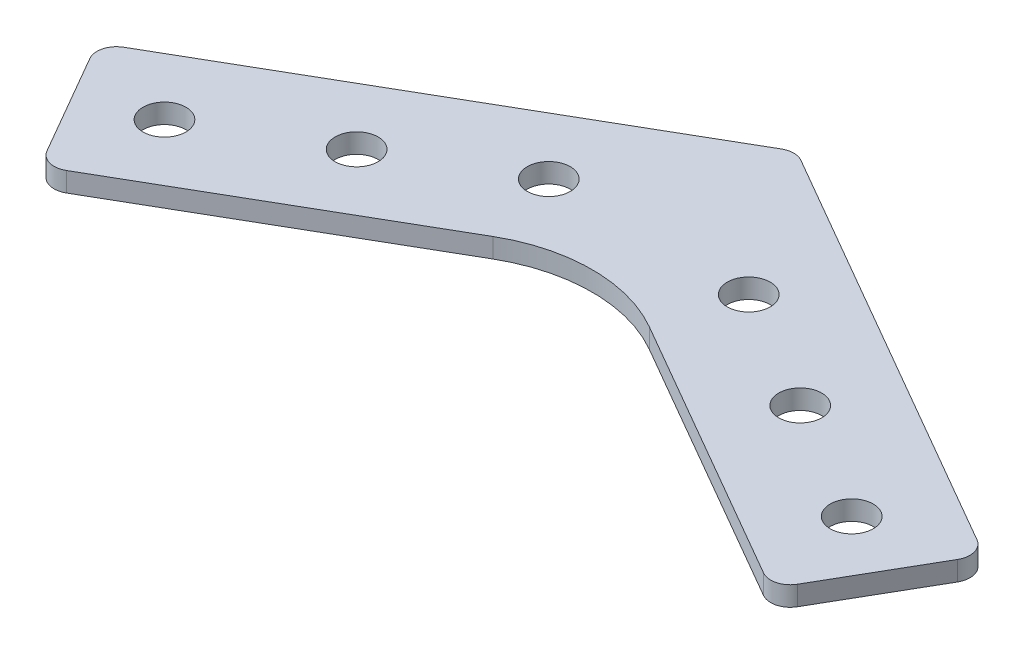
SolidWorks part; units mm, degrees
material "5052-H32"
ref_plane "Front Plane" through (0, 0, 0) normal (0, 0, 1) x (1, 0, 0)
ref_plane "Top Plane" through (0, 0, 0) normal (0, 1, 0) x (1, 0, 0)
ref_plane "Right Plane" through (0, 0, 0) normal (1, 0, 0) x (0, 0, -1)
sketch "Sketch1" plane through (0, 0, 0) normal (0, 1, 0) x (1, 0, 0)
  line L0 (-25.4, 14.6647) -> (0, 29.3294)
  line L5 (59.392, -34.29) -> (0, 0)
  line L6 (59.392, -34.29) -> (72.092, -12.293)
  line L7 (72.092, -12.293) -> (25.4, 14.6647)
  line L9 (0, 0) -> (-59.392, -34.29)
  line L11 (-25.4, 14.6647) -> (-72.092, -12.293)
  line L12 (-59.392, -34.29) -> (-72.092, -12.293)
  line L13 (0, 29.3294) -> (25.4, 14.6647)
  line L14 (-25.4, 14.6647) -> (0, 0) construction
  line L15 (25.4, 14.6647) -> (0, 0) construction
  line L16 (0, 0) -> (0, 29.3294) construction
  dimension "D1" = 25.4
  dimension "D2" = 25.4
  dimension "D5" = 120
  dimension "D3" = 68.58
  dimension "D4" = 68.58
extrude "Boss-Extrude1" add sketch "Sketch1" along normal blind 3.175 contours L0 L13 L7 L6 L5 L9 L12 L11
sketch "Sketch2" plane through (0, 3.175, 0) normal (0, 1, 0) x (1, 0, 0)
  line L0 (-72.092, -12.293) -> (-59.392, -34.29) construction
  line L1 (-55.8434, -17.5765) -> (-65.742, -23.2915) construction
  line L2 (72.092, -12.293) -> (59.392, -34.29) construction
  line L3 (55.8434, -17.5765) -> (65.742, -23.2915) construction
  circle A0 centre (-55.8434, -17.5765) radius 3.4925
  circle A1 centre (55.8434, -17.5765) radius 3.4925
  dimension "D1" = 6.985
  dimension "D2" = 11.43
sketch "Sketch7" plane through (0, 3.175, 0) normal (0, 1, 0) x (1, 0, 0)
  line L0 (-72.092, -12.293) -> (-59.392, -34.29) construction
  line L1 (-55.8434, -17.5765) -> (-65.742, -23.2915) construction
  line L2 (72.092, -12.293) -> (59.392, -34.29) construction
  line L3 (55.8434, -17.5765) -> (65.742, -23.2915) construction
  circle A0 centre (-55.8434, -17.5765) radius 3.4925
  circle A1 centre (55.8434, -17.5765) radius 3.4925
  dimension "D1" = 6.985
  dimension "D2" = 11.43
extrude "Cut-Extrude2" cut sketch "Sketch2" against normal blind 3.175 contours A0
pattern_linear "LPattern5" count 3 spacing 22.86 along (0.866, 0, -0.5) of "Cut-Extrude2"
extrude "Cut-Extrude3" cut sketch "Sketch7" against normal blind 3.175 contours A1
pattern_linear "LPattern6" count 3 spacing 22.86 along (-0.866, 0, -0.5) of "Cut-Extrude3"
fillet "Fillet1" radius 3.175 4 edges at (-72.092, 1.5875, 12.293) (-59.392, 1.5875, 34.29) (72.092, 1.5875, 12.293) (59.392, 1.5875, 34.29)
fillet "Fillet2" radius 25.4 1 edges at (0, 1.5875, 0)
fillet "Fillet3" radius 3.175 1 edges at (0, 1.5875, -29.3294)
equation "\"InnerAngle\"= \"AngleAB@Assem2.SLDASM\""
equation "\"StockThickness\"= .125in"
equation "\"HoleDiameter\"= .275in"
equation "\"BarWidth\"= 1in"
equation "\"HoleSpacing\"=0.9"
equation "\"AdditionalHoleCount\"= 3"
equation "\"D1@Sketch1\"=\"BarWidth\""
equation "\"D2@Sketch1\"= \"BarWidth\""
equation "\"WingLength\"= ( \"AdditionalHoleCount\" ) * \"HoleSpacing\""
equation "\"D5@Sketch1\"=\"InnerAngle\""
equation "\"D1@Boss-Extrude1\"=\"StockThickness\""
equation "\"D1@Sketch2\"=\"HoleDiameter\""
equation "\"D2@Sketch2\"=\"HoleSpacing\"/2"
equation "\"D3@LPattern5\"=\"HoleSpacing\""
equation "\"D1@LPattern5\"=\"AdditionalHoleCount\""
equation "\"D2@Sketch7\"=\"HoleSpacing\"/2"
equation "\"D1@Sketch7\"=\"HoleDiameter\""
equation "\"D3@LPattern6\"=\"HoleSpacing\""
equation "\"D1@LPattern6\"=\"AdditionalHoleCount\""
equation "\"D3@Sketch1\"=\"WingLength\""
equation "\"D4@Sketch1\"=\"WingLength\""
